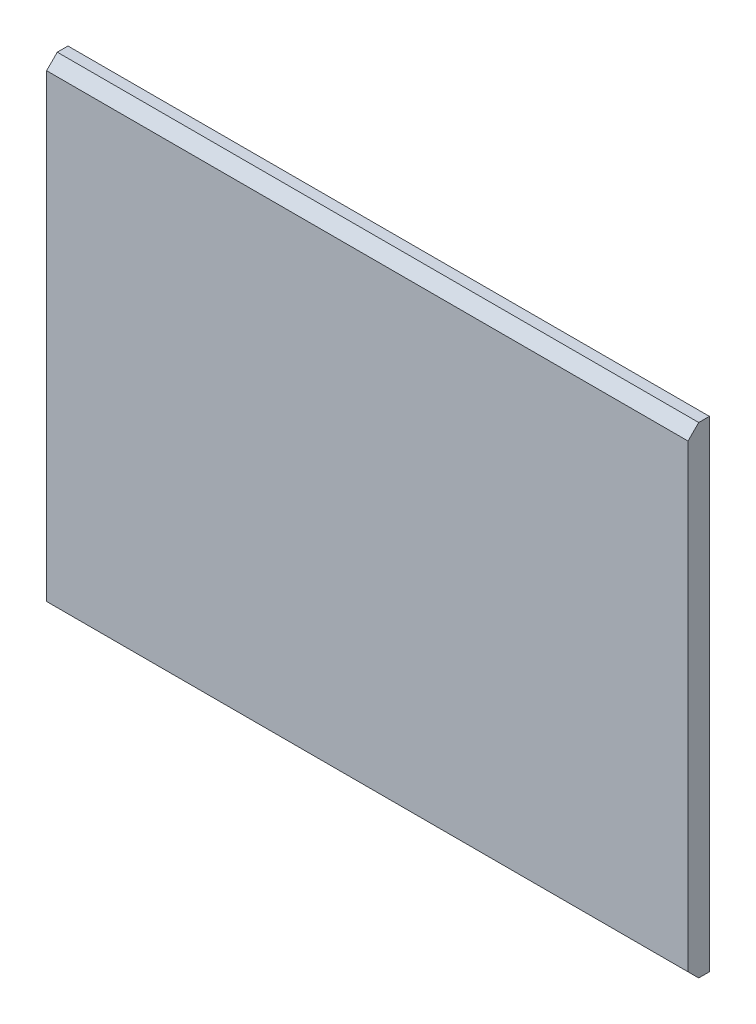
SolidWorks part; units mm, degrees
ref_plane "前视基准面" through (0, 0, 0) normal (0, 0, 1) x (1, 0, 0)
ref_plane "上视基准面" through (0, 0, 0) normal (0, 1, 0) x (1, 0, 0)
ref_plane "右视基准面" through (0, 0, 0) normal (1, 0, 0) x (0, 0, -1)
sketch "草图1" plane through (0, 0, 0) normal (0, 0, 1) x (1, 0, 0)
  line L1 (-150, 112.5) -> (150, 112.5)
  line L2 (-150, 112.5) -> (-150, -112.5)
  line L3 (-150, -112.5) -> (150, -112.5)
  line L4 (150, 112.5) -> (150, -112.5)
  line L5 (-150, 112.5) -> (150, -112.5) construction
  line L6 (-150, -112.5) -> (150, 112.5) construction
  point P0 (0, 0)
  dimension "D1" = 225
  dimension "D2" = 300
extrude "凸台-拉伸1" add sketch "草图1" along normal blind 10
chamfer "倒角1" distance 5 angle 45 2 edges at (0, -112.5, 10) (0, 112.5, 10)
